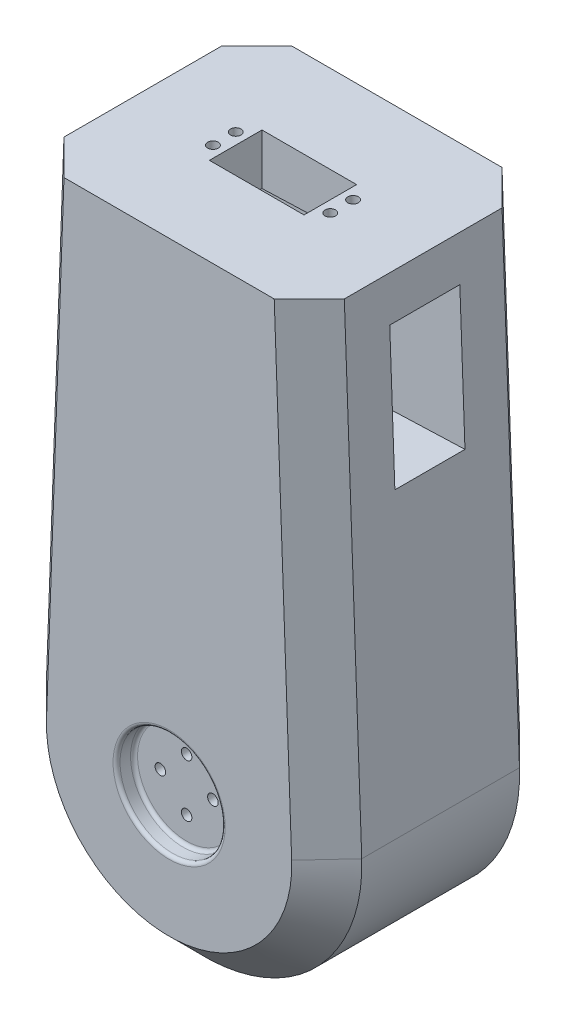
SolidWorks part; units mm, degrees
ref_plane "Front Plane" through (0, 0, 0) normal (0, 0, 1) x (1, 0, 0)
ref_plane "Top Plane" through (0, 0, 0) normal (0, 1, 0) x (1, 0, 0)
ref_plane "Right Plane" through (0, 0, 0) normal (1, 0, 0) x (0, 0, -1)
sketch "Sketch1" plane through (0, 0, 0) normal (0, 0, 1) x (1, 0, 0)
  line L0 (0, 0) -> (0, 660.9508) construction
  line L1 (-40, 137.5) -> (40, 137.5)
  line L2 (-40, 137.5) -> (-44.9699, 1.6451)
  line L3 (40, 137.5) -> (44.9699, 1.6451)
  arc A0 (-44.9699, 1.6451) -> (44.9699, 1.6451) centre (0, 0) ccw
  point P7 (0, 137.5)
  dimension "D1" = 90
  dimension "D2" = 80
  dimension "D3" = 137.5
extrude "Boss-Extrude1" add sketch "Sketch1" along normal blind 65
chamfer "Chamfer2" distance 10 6 edges at (-42.485, 69.5726, 0) (0, -45, 0) (42.485, 69.5726, 0) (-42.485, 69.5726, 65) (0, -45, 65) (42.485, 69.5726, 65)
sketch "Sketch2" plane through (0, 0, 65) normal (0, 0, 1) x (1, 0, 0)
  circle A0 centre (0, 0) radius 15
  dimension "D1" = 30
extrude "Cut-Extrude1" cut sketch "Sketch2" against normal blind 5
sketch "Sketch3" plane through (0, 0, 60) normal (0, 0, 1) x (1, 0, 0)
  line L0 (-27.1935, 0) -> (27.1935, 0) construction
  line L1 (0, 23.7134) -> (0, -23.7134) construction
  circle A0 centre (0, 7.5) radius 1.5
  circle A1 centre (7.5, 0) radius 1.5
  circle A2 centre (0, -7.5) radius 1.5
  circle A3 centre (-7.5, 0) radius 1.5
  point P5 (0, 0)
  point P9 (0, 0)
  point P20 (0, 0)
  dimension "D1" = 3
  dimension "D2" = 7.5
  dimension "D3" = 4
extrude "Cut-Extrude2" cut sketch "Sketch3" against normal blind 7.5
fillet "Fillet1" radius 1 2 edges at (15, 0, 60) (15, 0, 65)
sketch "Sketch4" plane through (44.9699, 1.6451, 0) normal (0.9993, 0.0366, 0) x (0, 0, -1)
  line L0 (-32.5, -851.4234) -> (-32.5, 49148.5766) construction
  line L1 (-55, 135.9458) -> (-10, 135.9458) construction
  line L3 (-42.5, 123.4458) -> (-22.5, 123.4458)
  line L4 (-42.5, 123.4458) -> (-42.5, 83.4458)
  line L5 (-42.5, 83.4458) -> (-22.5, 83.4458)
  line L6 (-22.5, 123.4458) -> (-22.5, 83.4458)
  line L7 (-42.5, 123.4458) -> (-22.5, 83.4458) construction
  line L8 (-42.5, 83.4458) -> (-22.5, 123.4458) construction
  point P1 (-32.5, 103.4458)
  point P5 (-32.5, 135.9458)
  dimension "D1" = 40
  dimension "D2" = 20
  dimension "D3" = 32.5
extrude "Cut-Extrude3" cut sketch "Sketch4" against normal through all
sketch "Sketch5" plane through (0, 137.5, 0) normal (0, 1, 0) x (1, 0, 0)
  line L0 (-1040, -32.5) -> (48960, -32.5) construction
  line L1 (-40, -55) -> (-40, -10) construction
  line L2 (0, -1040) -> (0, 48960) construction
  line L3 (-13.5, -25) -> (13.5, -25)
  line L4 (-13.5, -25) -> (-13.5, -40)
  line L5 (-13.5, -40) -> (13.5, -40)
  line L6 (13.5, -25) -> (13.5, -40)
  line L7 (-13.5, -25) -> (13.5, -40) construction
  line L8 (-13.5, -40) -> (13.5, -25) construction
  circle A0 centre (-16.75, -29.25) radius 1.5
  circle A1 centre (-16.75, -35.75) radius 1.5
  circle A2 centre (16.75, -35.75) radius 1.5
  circle A3 centre (16.75, -29.25) radius 1.5
  point P1 (0, -32.5)
  point P5 (-40, -32.5)
  point P18 (0, -40)
  dimension "D4" = 3
  dimension "D5" = 3.25
  dimension "D1" = 27
  dimension "D2" = 15
  dimension "D3" = 40
  dimension "D6" = 3.25
extrude "Cut-Extrude5" cut sketch "Sketch5" against normal up to surface (13.4778 mm away)
sketch "Sketch6" plane through (0, 137.5, 0) normal (0, 1, 0) x (1, 0, 0)
  line L0 (-13.5, -32.5) -> (13.5, -32.5) construction
  line L1 (-13.5, -25) -> (-13.5, -40) construction
  line L2 (13.5, -40) -> (13.5, -25) construction
  circle A1 centre (0, -32.5) radius 3.75
  dimension "D1" = 7.5
